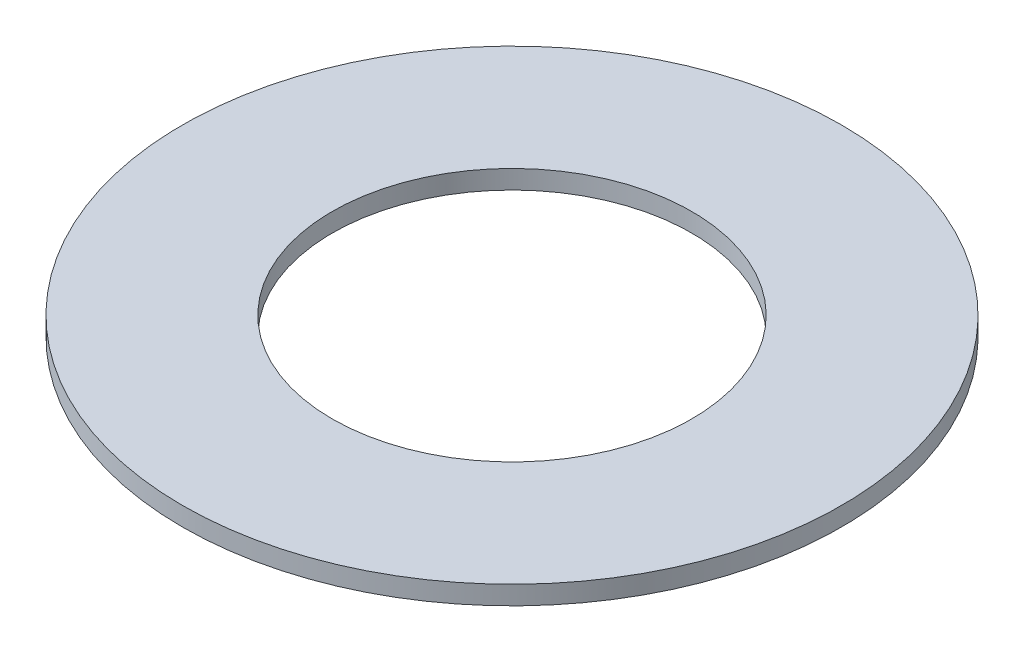
SolidWorks part; units mm, degrees
ref_plane "Front Plane" through (0, 0, 0) normal (0, 0, 1) x (1, 0, 0)
ref_plane "Top Plane" through (0, 0, 0) normal (0, 1, 0) x (1, 0, 0)
ref_plane "Right Plane" through (0, 0, 0) normal (1, 0, 0) x (0, 0, -1)
sketch "Sketch2" plane through (0, 0, 0) normal (0, 1, 0) x (1, 0, 0)
  circle A0 centre (0, 0) radius 110
  dimension "D1" = 220
extrude "Boss-Extrude1" add sketch "Sketch2" along normal blind 6.25
sketch "Sketch3" plane through (0, 6.25, 0) normal (0, 1, 0) x (1, 0, 0)
  circle A0 centre (0, 0) radius 60
  dimension "D1" = 120
extrude "Cut-Extrude1" cut sketch "Sketch3" against normal blind 6.25
